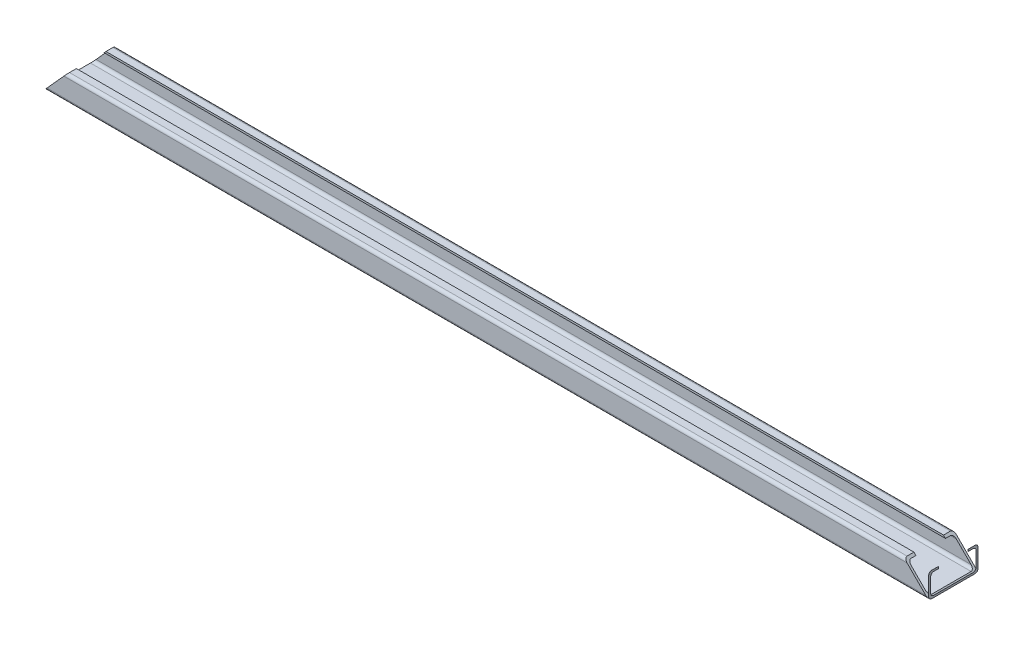
SolidWorks part; units mm, degrees
material "AISI 1045 Aço, trefilado"
ref_plane "Plano frontal" through (0, 0, 0) normal (0, 0, 1) x (1, 0, 0)
ref_plane "Plano superior" through (0, 0, 0) normal (0, 1, 0) x (1, 0, 0)
ref_plane "Plano direito" through (0, 0, 0) normal (1, 0, 0) x (0, 0, -1)
sketch "Esboço1" plane through (0, 0, 0) normal (1, 0, 0) x (0, 0, -1)
  line L0 (-46, 21) -> (-46, -21)
  line L1 (-50, 25) -> (-30, 25)
  line L2 (-50, 25) -> (-50, -25)
  line L3 (-50, -25) -> (50, -25)
  line L4 (50, 25) -> (50, -25)
  line L5 (-50, 25) -> (50, -25) construction
  line L6 (-50, -25) -> (50, 25) construction
  line L7 (-46, -21) -> (46, -21)
  line L8 (46, 21) -> (46, -21)
  line L9 (-46, 21) -> (-30, 21)
  line L10 (-30, 25) -> (-30, 21)
  line L13 (30, 25) -> (30, 21)
  line L14 (30, 21) -> (46, 21)
  line L15 (-46, 21) -> (46, 21) construction
  line L16 (30, 25) -> (50, 25)
  line L17 (-50, 25) -> (50, 25) construction
  point P0 (0, 0)
  dimension "D1" = 100
  dimension "D2" = 50
  dimension "D4" = 20
  dimension "D5" = 20
  dimension "D3" = 4
extrude "Ressalto-extrusão1" add sketch "Esboço1" along normal blind 1800
fillet "Filete1" radius 6 8 edges at (900, 21, -46) (900, 21, 46) (900, 25, 50) (900, 25, -50) (900, -25, -50) (900, -21, -46) (900, -21, 46) (900, -25, 50)
sketch "Esboço3" plane through (0, 0, 0) normal (0, 0, 1) x (1, 0, 0)
  line L0 (0, -25) -> (184.7676, 159.7676)
  line L1 (184.7676, 159.7676) -> (-208.6154, 104.9391)
  line L2 (-208.6154, 104.9391) -> (0, -25)
  line L3 (0, 19) -> (0, -19) construction
  line L4 (1800, -25) -> (1477.7073, 297.2927)
  line L5 (1477.7073, 297.2927) -> (1799.3834, 297.2927)
  line L6 (1799.3834, 297.2927) -> (1800, -25)
  line L7 (1800, -25) -> (0, -25) construction
  dimension "D1" = 45
  dimension "D2" = 45
extrude "Corte-extrusão1" cut sketch "Esboço3" against normal mid plane 100
sketch "Esboço4" plane through (0, 0, 0) normal (0, 0, 1) x (1, 0, 0)
  line L4 (50, 25) -> (-16.2356, -48.5621)
  line L5 (-16.2356, -48.5621) -> (-42.1297, -17.7158)
  line L6 (-42.1297, -17.7158) -> (50, 25)
  line L7 (6, -19) -> (44, 19) construction
  dimension "D1" = 3
extrude "Corte-extrusão2" cut sketch "Esboço4" against normal mid plane 100
